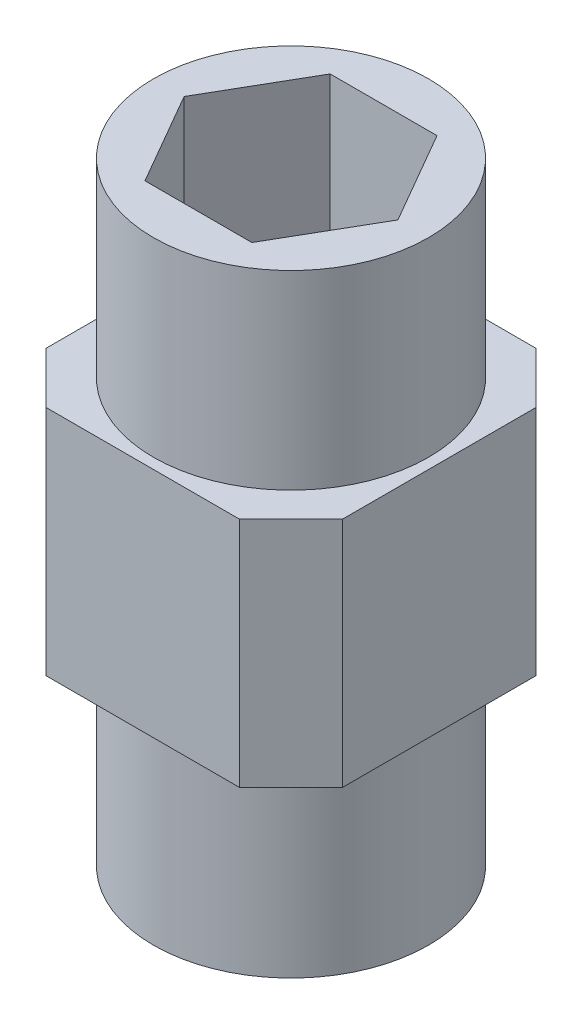
SolidWorks part; units mm, degrees
ref_plane "Front Plane" through (0, 0, 0) normal (0, 0, 1) x (1, 0, 0)
ref_plane "Top Plane" through (0, 0, 0) normal (0, 1, 0) x (1, 0, 0)
ref_plane "Right Plane" through (0, 0, 0) normal (1, 0, 0) x (0, 0, -1)
sketch "Sketch1" plane through (0, 0, 0) normal (0, 1, 0) x (1, 0, 0)
  line L1 (7.3612, 0) -> (3.6806, 6.375)
  line L2 (3.6806, 6.375) -> (-3.6806, 6.375)
  line L3 (-3.6806, 6.375) -> (-7.3612, 0)
  line L4 (-7.3612, 0) -> (-3.6806, -6.375)
  line L5 (-3.6806, -6.375) -> (3.6806, -6.375)
  line L6 (3.6806, -6.375) -> (7.3612, 0)
  circle A0 centre (0, 0) radius 9.475
  circle A1 centre (0, 0) radius 6.375 construction
  dimension "D1" = 18.95
  dimension "D2" = 12.75
extrude "Boss-Extrude1" add sketch "Sketch1" along normal blind 13.1
sketch "Sketch2" plane through (0, 0, 0) normal (0, 1, 0) x (1, 0, 0)
  line L0 (-10.2, 6.6645) -> (-6.6645, 10.2)
  line L1 (-6.6645, -10.2) -> (6.6645, -10.2)
  line L2 (-10.2, -6.6645) -> (-10.2, 6.6645)
  line L3 (-6.6645, 10.2) -> (6.6645, 10.2)
  line L4 (10.2, -6.6645) -> (10.2, 6.6645)
  line L5 (3.6806, 6.375) -> (-3.6806, 6.375) construction
  line L6 (-3.6806, 6.375) -> (-7.3612, 0) construction
  line L8 (10.2, 6.6645) -> (6.6645, 10.2)
  line L10 (10.2, -6.6645) -> (6.6645, -10.2)
  line L11 (-10.2, -6.6645) -> (-6.6645, -10.2)
  line L12 (-7.3612, 0) -> (-3.6806, -6.375) construction
  line L13 (-3.6806, -6.375) -> (3.6806, -6.375) construction
  line L14 (3.6806, -6.375) -> (7.3612, 0) construction
  line L15 (7.3612, 0) -> (3.6806, 6.375) construction
  line L16 (3.6806, 6.375) -> (-3.6806, 6.375)
  line L17 (-3.6806, 6.375) -> (-7.3612, 0)
  line L18 (-7.3612, 0) -> (-3.6806, -6.375)
  line L19 (-3.6806, -6.375) -> (3.6806, -6.375)
  line L20 (3.6806, -6.375) -> (7.3612, 0)
  line L21 (7.3612, 0) -> (3.6806, 6.375)
  point P0 (0, 0)
  dimension "D1" = 20.4
  dimension "D2" = 20.4
  dimension "D3" = 5
  dimension "D4" = 45
extrude "Boss-Extrude3" add sketch "Sketch2" against normal blind 16
ref_plane "Plane1" through (0, -8, 0) normal (0, 1, 0) x (1, 0, 0)
mirror "Mirror1" about plane through (0, -8, 0) normal (0, 1, 0) of "Boss-Extrude1"
